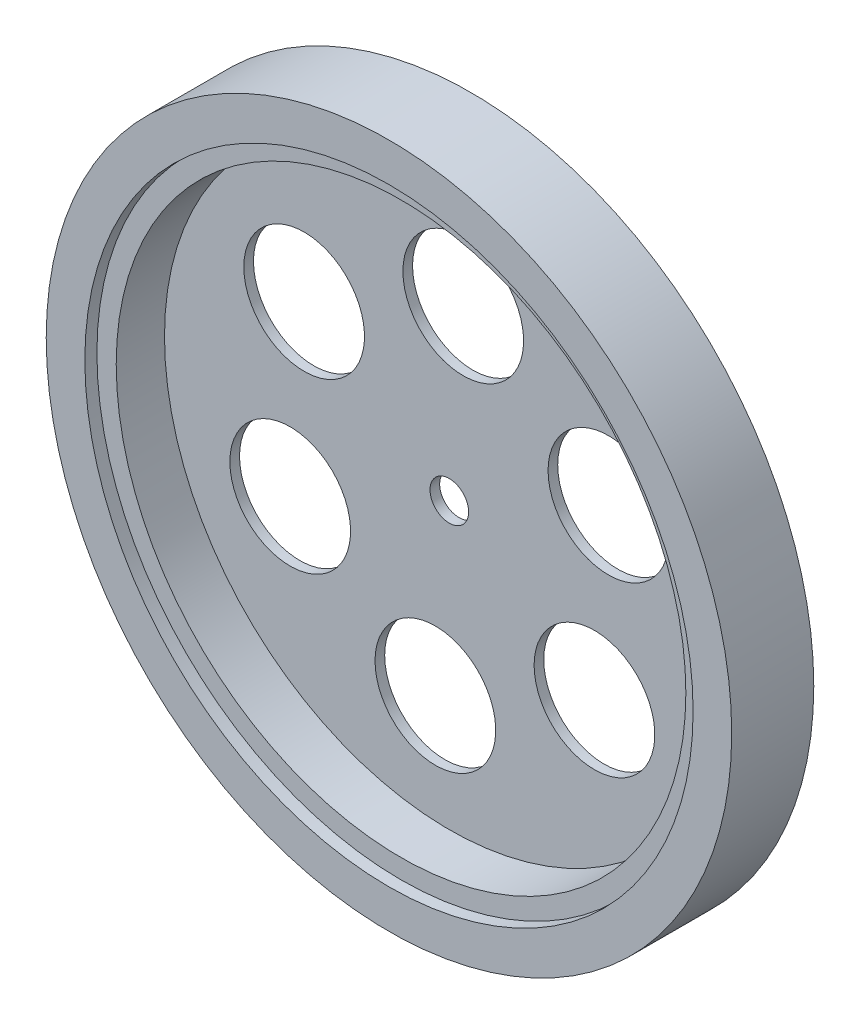
SolidWorks part; units mm, degrees
ref_plane "Front Plane" through (0, 0, 0) normal (0, 0, 1) x (1, 0, 0)
ref_plane "Top Plane" through (0, 0, 0) normal (0, 1, 0) x (1, 0, 0)
ref_plane "Right Plane" through (0, 0, 0) normal (1, 0, 0) x (0, 0, -1)
sketch "Sketch1" plane through (0, 0, 0) normal (0, 0, 1) x (1, 0, 0)
  circle A0 centre (0, 0) radius 33
  circle A1 centre (0, 0) radius 2
  circle A2 centre (0, 0) radius 29.5
  dimension "D1" = 66
  dimension "D2" = 4
  dimension "D3" = 3.5
extrude "Boss-Extrude1" add sketch "Sketch1" along normal blind 6 contours A0 A2
sketch "Sketch2" plane through (0, 0, 0) normal (0, 0, -1) x (-1, 0, 0)
  circle A0 centre (0, 0) radius 33
  circle A1 centre (0, 0) radius 2
  dimension "D1" = 4
  dimension "D2" = 66
extrude "Boss-Extrude2" add sketch "Sketch2" against normal blind 1
sketch "Sketch3" plane through (0, 0, 0) normal (0, 0, -1) x (-1, 0, 0)
  line L0 (0, 0) -> (1.4442, -18.1928)
  circle A0 centre (0, 0) radius 33
  circle A1 centre (1.4442, -18.1928) radius 6.25
  circle A2 centre (0, 0) radius 18.25
  dimension "D1" = 66
  dimension "D3" = 12.5
  dimension "D2" = 18.25
extrude "Cut-Extrude2" cut sketch "Sketch3" against normal blind 7
pattern_circular "CirPattern1" count 6 every 60 about axis through (0, 0, 0) along (0, 0, 1) of "Cut-Extrude2"
sketch "Sketch4" plane through (0, 0, 0) normal (0, 0, -1) x (-1, 0, 0)
  circle A0 centre (0, 0) radius 31.5
  circle A1 centre (0, 0) radius 35.5
  dimension "D1" = 4
  dimension "D2" = 71
extrude "Boss-Extrude3" add sketch "Sketch4" against normal blind 7.25 and the other way blind 1.25
